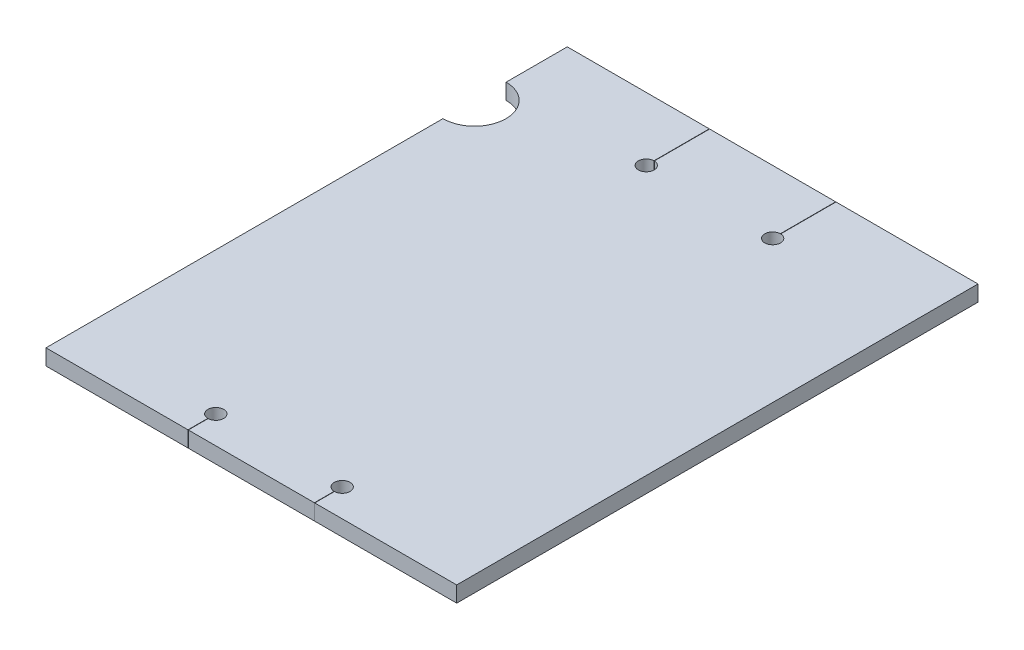
SolidWorks part; units mm, degrees
ref_plane "front" through (0, 0, 0) normal (0, 0, 1) x (1, 0, 0)
ref_plane "top" through (0, 0, 0) normal (0, 1, 0) x (1, 0, 0)
ref_plane "right" through (0, 0, 0) normal (1, 0, 0) x (0, 0, -1)
sketch "Sketch1" plane through (0, 0, 0) normal (0, 1, 0) x (1, 0, 0)
  line L0 (171.45, 469.9) -> (-19.05, 469.9)
  line L1 (-180.975, 482.6) -> (180.975, 482.6)
  line L2 (-196.85, 466.725) -> (-196.85, 15.875)
  line L3 (-180.975, 0) -> (180.975, 0)
  line L4 (196.85, 466.725) -> (196.85, 15.875)
  line L5 (-44.45, 444.5) -> (-44.45, 368.3)
  line L6 (-59.4796, 345.1135) -> (-111.9704, 321.6365)
  line L7 (-127, 298.45) -> (-127, 95.25)
  line L8 (-117.3758, 75.3431) -> (-79.4742, 45.3069)
  line L9 (-69.85, 25.4) -> (-69.85, 0)
  line L10 (0, 60.6632) -> (0, 195.7443) construction
  line L15 (69.85, 25.4) -> (69.85, 0)
  line L16 (117.3758, 75.3431) -> (79.4742, 45.3069)
  line L17 (127, 298.45) -> (127, 95.25)
  line L18 (59.4796, 345.1135) -> (111.9704, 321.6365)
  line L19 (44.45, 368.3) -> (44.45, 381)
  line L20 (69.85, 406.4) -> (171.45, 406.4)
  line L21 (184.15, 419.1) -> (184.15, 457.2)
  arc A0 (-19.05, 469.9) -> (-44.45, 444.5) centre (-19.05, 444.5) ccw
  arc A1 (-44.45, 368.3) -> (-59.4796, 345.1135) centre (-69.85, 368.3) cw
  arc A2 (-111.9704, 321.6365) -> (-127, 298.45) centre (-101.6, 298.45) ccw
  arc A3 (-127, 95.25) -> (-117.3758, 75.3431) centre (-101.6, 95.25) ccw
  arc A4 (-79.4742, 45.3069) -> (-69.85, 25.4) centre (-95.25, 25.4) cw
  arc A7 (79.4742, 45.3069) -> (69.85, 25.4) centre (95.25, 25.4) ccw
  arc A8 (127, 95.25) -> (117.3758, 75.3431) centre (101.6, 95.25) cw
  arc A9 (111.9704, 321.6365) -> (127, 298.45) centre (101.6, 298.45) cw
  arc A10 (44.45, 368.3) -> (59.4796, 345.1135) centre (69.85, 368.3) ccw
  arc A13 (44.45, 381) -> (69.85, 406.4) centre (69.85, 381) cw
  arc A14 (171.45, 406.4) -> (184.15, 419.1) centre (171.45, 419.1) ccw
  arc A15 (171.45, 469.9) -> (184.15, 457.2) centre (171.45, 457.2) cw
  circle A16 centre (152.4, 431.8) radius 22.225
  arc A17 (180.975, 0) -> (196.85, 15.875) centre (180.975, 15.875) ccw
  arc A18 (180.975, 482.6) -> (196.85, 466.725) centre (180.975, 466.725) cw
  arc A19 (-180.975, 482.6) -> (-196.85, 466.725) centre (-180.975, 466.725) ccw
  arc A20 (-196.85, 15.875) -> (-180.975, 0) centre (-180.975, 15.875) ccw
  dimension "D3" = 25.4
  dimension "D4" = 25.4
  dimension "D5" = 25.4
  dimension "D6" = 25.4
  dimension "D7" = 25.4
  dimension "D8" = 25.4
  dimension "D9" = 25.4
  dimension "D10" = 12.7
  dimension "D11" = 12.7
  dimension "D14" = 44.45
  dimension "D15" = 15.875
  dimension "D1" = 393.7
  dimension "D2" = 203.2
  dimension "D12" = 12.7
  dimension "D13" = 12.7
  dimension "D16" = 12.7
  dimension "D17" = 69.85
  dimension "D18" = 69.85
  dimension "D19" = 88.9
  dimension "D20" = 63.5
  dimension "D21" = 139.7
  dimension "D22" = 254
  dimension "D23" = 482.6
  dimension "D24" = 431.8
  dimension "D25" = 152.4
sketch "Sketch2" plane through (0, 0, 0) normal (0, 1, 0) x (1, 0, 0)
  line L1 (-165.1, 25.4) -> (165.1, 25.4)
  line L2 (-165.1, 25.4) -> (-165.1, 457.2)
  line L3 (-165.1, 457.2) -> (165.1, 457.2)
  line L4 (180.975, 482.6) -> (-180.975, 482.6)
  line L5 (-196.85, 466.725) -> (-196.85, 15.875)
  line L6 (-180.975, 0) -> (180.975, 0)
  line L7 (196.85, 15.875) -> (196.85, 466.725)
  line L8 (180.975, 482.6) -> (-180.975, 482.6) construction
  line L9 (-196.85, 466.725) -> (-196.85, 15.875) construction
  line L10 (-180.975, 0) -> (180.975, 0) construction
  line L11 (196.85, 15.875) -> (196.85, 466.725) construction
  line L12 (165.1, 25.4) -> (165.1, 457.2)
  arc A4 (180.975, 0) -> (196.85, 15.875) centre (180.975, 15.875) ccw
  arc A5 (180.975, 0) -> (196.85, 15.875) centre (180.975, 15.875) ccw construction
  arc A6 (-196.85, 15.875) -> (-180.975, 0) centre (-180.975, 15.875) ccw
  arc A7 (-196.85, 15.875) -> (-180.975, 0) centre (-180.975, 15.875) ccw construction
  arc A8 (-180.975, 482.6) -> (-196.85, 466.725) centre (-180.975, 466.725) ccw
  arc A9 (-180.975, 482.6) -> (-196.85, 466.725) centre (-180.975, 466.725) ccw construction
  arc A10 (196.85, 466.725) -> (180.975, 482.6) centre (180.975, 466.725) ccw
  arc A11 (196.85, 466.725) -> (180.975, 482.6) centre (180.975, 466.725) ccw construction
  point P9 (0, 25.4)
  dimension "D2" = 31.75
  dimension "D3" = 25.4
  dimension "D4" = 25.4
  dimension "D1" = 0
extrude "Extrude2" add sketch "Sketch2" along normal blind 12.7
sketch "Sketch3" plane through (0, 0, 0) normal (0, 1, 0) x (1, 0, 0)
  line L1 (-231.561, 38.1) -> (231.561, 38.1)
  line L2 (-231.561, 38.1) -> (-231.561, -48.6359)
  line L3 (-231.561, -48.6359) -> (231.561, -48.6359)
  line L4 (231.561, 38.1) -> (231.561, -48.6359)
  point P4 (0, -48.6359)
  dimension "D1" = 38.1
extrude "Cut-Extrude1" cut sketch "Sketch3" along normal through all
sketch "Sketch4" plane through (0, 0, 0) normal (0, 1, 0) x (1, 0, 0)
  line L0 (-211.1502, 488.95) -> (-211.1502, 318.6317) construction
  line L1 (-180.975, 482.6) -> (180.975, 482.6) construction
  line L2 (-165.1, 457.2) -> (-165.1, 38.1) construction
  line L5 (-223.49, 404.8252) -> (-139.7, 404.8252) construction
  line L6 (-223.49, 404.8252) -> (-223.49, 360.3752) construction
  line L7 (-223.49, 360.3752) -> (-139.7, 360.3752) construction
  line L8 (-139.7, 404.8252) -> (-139.7, 360.3752) construction
  circle A0 centre (-165.1, 382.6002) radius 25.4
  point P11 (-139.7, 382.6002)
  dimension "D3" = 50.8
  dimension "D1" = 99.9998
  dimension "D2" = 25.4
  dimension "D5" = 44.45
extrude "Cut-Extrude2" cut sketch "Sketch4" along normal through all
sketch "Sketch5" plane through (0, 0, 0) normal (0, 1, 0) x (1, 0, 0)
  line L0 (0, 0) -> (0, 64.0117) construction
  line L1 (-180.975, 0) -> (180.975, 0) construction
  line L2 (180.975, 482.6) -> (-180.975, 482.6) construction
  line L4 (-50.927, 495.6048) -> (-50.673, 495.6048)
  line L5 (-50.927, 495.6048) -> (-50.927, 412.7487)
  line L7 (-50.673, 495.6048) -> (-50.673, 412.7487)
  line L10 (50.673, 497.3669) -> (50.927, 497.3669)
  line L11 (50.673, 497.3669) -> (50.673, 412.7487)
  line L13 (50.927, 497.3669) -> (50.927, 412.7487)
  line L15 (-50.673, 53.9763) -> (-50.673, 30.4458)
  line L18 (-50.927, 30.4458) -> (-50.673, 30.4458)
  line L20 (-50.927, 53.9763) -> (-50.927, 30.4458)
  line L21 (50.927, 53.9763) -> (50.927, 31.394)
  line L24 (50.673, 31.394) -> (50.927, 31.394)
  line L26 (50.673, 53.9763) -> (50.673, 31.394)
  arc A1 (-50.927, 412.7487) -> (-50.673, 412.7487) centre (-50.8, 406.4) ccw
  arc A3 (50.673, 53.9763) -> (50.927, 53.9763) centre (50.8, 60.325) cw
  arc A5 (-50.673, 53.9763) -> (-50.927, 53.9763) centre (-50.8, 60.325) ccw
  arc A6 (50.927, 412.7487) -> (50.673, 412.7487) centre (50.8, 406.4) cw
  point P19 (-50.8, 495.6048)
  point P26 (50.8, 497.3669)
  point P32 (-50.8, 30.4458)
  point P43 (50.8, 31.394)
  dimension "D3" = 6.35
  dimension "D5" = 12.7
  dimension "D12" = 12.7
  dimension "D1" = 50.8
  dimension "D2" = 60.325
  dimension "D4" = 76.2
  dimension "D6" = 0.254
  dimension "D9" = 0.254
  dimension "D10" = 0.254
  dimension "D13" = 0.254
extrude "Cut-Extrude3" cut sketch "Sketch5" along normal through all
